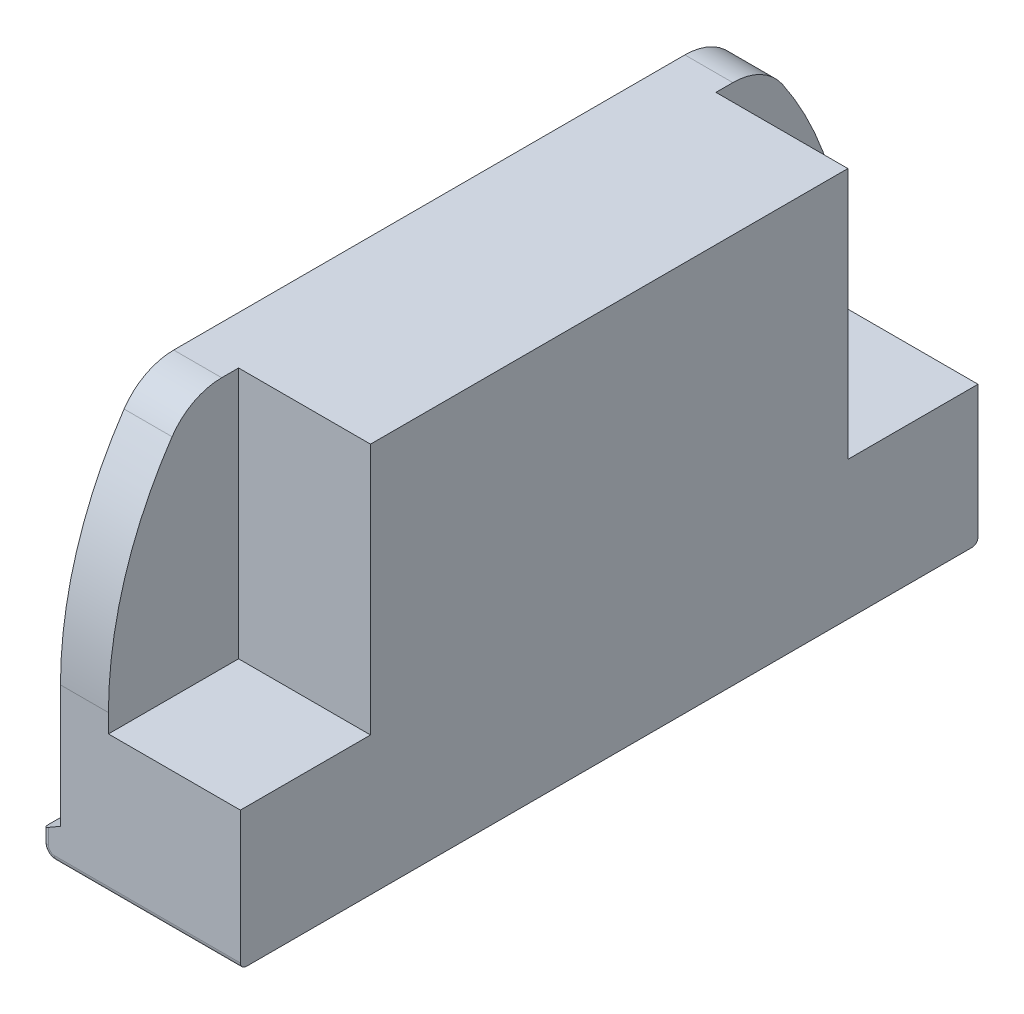
SolidWorks part; units mm, degrees
ref_plane "Front Plane" through (0, 0, 0) normal (0, 0, 1) x (1, 0, 0)
ref_plane "Top Plane" through (0, 0, 0) normal (0, 1, 0) x (1, 0, 0)
ref_plane "Right Plane" through (0, 0, 0) normal (1, 0, 0) x (0, 0, -1)
sketch "Sketch1" plane through (0, 0, 0) normal (0, 0, 1) x (1, 0, 0)
  line L0 (0, 0) -> (0.3, 0.1732)
  line L1 (0.3, 6.1075) -> (0.3, 1.7816)
  line L2 (0.3, 6.1075) -> (3.3, 6.1075)
  line L3 (3.3, 6.1075) -> (3.3, 0.6468)
  line L4 (0.3, 1.7816) -> (0.3, 0.1732)
  line L5 (0.3, 0.9774) -> (0.15, 0.0866) construction
  line L6 (2.3013, 0.5964) -> (0.3, 0.1732) construction
  line L7 (1.3155, -0.3379) -> (0.3, 0.1732) construction
  line L8 (1.3155, -0.3379) -> (3.3, 0.6468) construction
  line L9 (3.3, 0.6468) -> (3.3, -0.4)
  line L10 (3.3, -0.4) -> (0.2, -0.4)
  line L11 (0, 0) -> (0, -0.2)
  arc A0 (3.3, 0.6468) -> (2.3013, 0.5964) centre (8.5649, -113.5554) ccw construction
  arc A1 (0.2, -0.4) -> (0, -0.2) centre (0.2, -0.2) cw
  point P9 (0.3, 1.7816)
  point P10 (0, -3.0581)
  point P17 (0, -0.4)
  dimension "D1" = 0.3464
  dimension "D2" = 114.3235
  dimension "D3" = 5.9342
  dimension "D6" = 1
  dimension "D12" = 0.2
  dimension "D4" = 3
  dimension "D5" = 5.4606
  dimension "D7" = 1.6084
  dimension "D8" = 0.9033
  dimension "D9" = 1.1369
  dimension "D10" = 2.2154
  dimension "D11" = 0.4
extrude "Boss-Extrude1" add sketch "Sketch1" along normal blind 12.3
sketch "Sketch2" plane through (0, 6.1075, 0) normal (0, 1, 0) x (1, 0, 0)
  line L0 (3.3, -6.15) -> (0.3, -6.15) construction
  line L1 (3.3, 0) -> (1.1, 0)
  line L2 (3.3, 0) -> (3.3, -2.17)
  line L3 (3.3, -2.17) -> (1.1, -2.17)
  line L4 (1.1, 0) -> (1.1, -2.17)
  line L5 (3.3, -12.3) -> (3.3, 0) construction
  line L6 (0.3, -12.3) -> (0.3, 0) construction
  line L7 (3.3, -10.13) -> (1.1, -10.13)
  line L8 (3.3, -12.3) -> (3.3, -10.13)
  line L9 (3.3, -12.3) -> (1.1, -12.3)
  line L10 (1.1, -12.3) -> (1.1, -10.13)
  dimension "D1" = 2.17
  dimension "D2" = 2.2
extrude "Cut-Extrude1" cut sketch "Sketch2" against normal blind 4.2
sketch "Sketch4" plane through (0.3, 0, 0) normal (-1, 0, 0) x (0, 0, 1)
  line L0 (12.3, 0.1732) -> (12.3, 2.2159) construction
  line L1 (12.3, 6.1075) -> (12.3, 0.1732) construction
  line L2 (1.8884, 6.1075) -> (10.4116, 6.1075) construction
  line L3 (12.3, 6.1075) -> (0, 6.1075) construction
  line L4 (6.15, 6.1075) -> (6.15, 0.1732) construction
  line L5 (12.3, 0.1732) -> (0, 0.1732) construction
  line L6 (11.2391, 5.669) -> (10.4116, 6.1075) construction
  line L7 (10.4116, 6.1075) -> (12.3, 6.1075)
  line L8 (12.3, 6.1075) -> (12.3, 2.2159)
  line L9 (1.8884, 6.1075) -> (0, 6.1075)
  line L10 (0, 6.1075) -> (0, 2.2159)
  arc A0 (12.3, 2.2159) -> (11.2391, 5.669) centre (6.1496, 2.2159) ccw
  arc A1 (11.2391, 5.669) -> (10.4116, 6.1075) centre (10.4119, 5.1078) ccw
  arc A2 (1.0609, 5.669) -> (1.8884, 6.1075) centre (1.8881, 5.1078) cw
  arc A3 (0, 2.2159) -> (1.0609, 5.669) centre (6.1504, 2.2159) cw
  dimension "D1" = 8.5232
  dimension "D2" = 0.9365
  dimension "D3" = 3.6124
  dimension "D4" = 3.6665
extrude "Cut-Extrude3" cut sketch "Sketch4" against normal up to surface (0.8 mm away) up to face at (1.1, 4.0075, 11.215)
sketch "Sketch5" plane through (0.3, 0, 0) normal (-1, 0, 0) x (0, 0, 1)
  line L0 (6.15, 1.7816) -> (6.15, 0.1732) construction
  line L1 (4.65, 2.7816) -> (7.65, 2.7816)
  line L2 (4.65, 2.7816) -> (4.65, 1.7816)
  line L3 (4.65, 1.7816) -> (7.65, 1.7816)
  line L4 (7.65, 2.7816) -> (7.65, 1.7816)
  line L5 (12.3, 0.1732) -> (0, 0.1732) construction
  dimension "D1" = 1.6084
  dimension "D2" = 3
  dimension "D3" = 1
extrude "Boss-Extrude2" add sketch "Sketch5" along normal blind 0.4
sketch "Sketch6" plane through (0, 0, 7.65) normal (0, 0, 1) x (1, 0, 0)
  line L0 (0.3, 2.7816) -> (0.3, 4.3732)
  line L1 (0.3, 5.669) -> (0.3, 2.2159) construction
  line L2 (0.3, 4.3732) -> (-0.1, 2.7816)
  line L3 (-0.1, 2.7816) -> (0.3, 2.7816)
  dimension "D1" = 1.5916
extrude "Boss-Extrude3" add sketch "Sketch6" against normal up to surface (3 mm away) up to face at (0.1, 2.2816, 4.65)
fillet "Fillet1" radius 0.1 6 edges at (0, -0.1, 12.3) (0.0586, -0.3414, 12.3) (1.75, -0.4, 12.3) (0, -0.1, 0) (0.0586, -0.3414, 0) (1.75, -0.4, 0)
